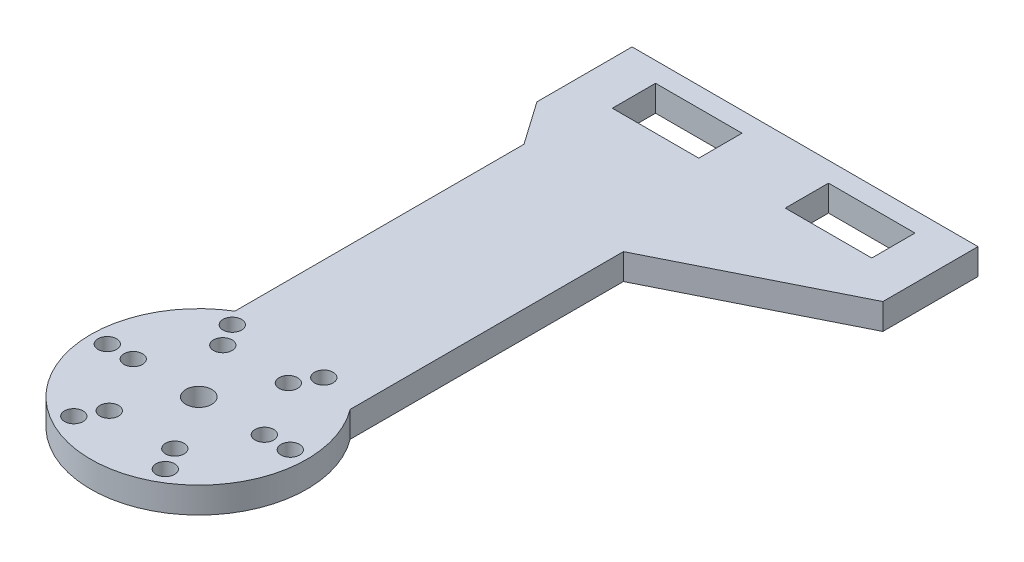
SolidWorks part; units mm, degrees
ref_plane "前视基准面" through (0, 0, 0) normal (0, 0, 1) x (1, 0, 0)
ref_plane "上视基准面" through (0, 0, 0) normal (0, 1, 0) x (1, 0, 0)
ref_plane "右视基准面" through (0, 0, 0) normal (1, 0, 0) x (0, 0, -1)
sketch "草图1" plane through (0, 0, 0) normal (0, 1, 0) x (1, 0, 0)
  line L0 (-143.0757, 0) -> (143.0757, 0) construction
  line L1 (0, 82.2875) -> (0, -82.2875) construction
  line L2 (-6.5, 10.6771) -> (-6.5, 44.1)
  line L3 (10, 7.5) -> (10, 39.1)
  line L4 (-6.5, 44.1) -> (-10, 49.0985)
  line L5 (-10, 49.0985) -> (-10, 60.1)
  line L6 (-10, 60.1) -> (30, 60.1)
  line L7 (30, 60.1) -> (30, 49.1)
  line L8 (30, 49.1) -> (10, 39.1)
  line L9 (-5, 57.8142) -> (-5, 52.8142)
  line L10 (-5, 52.8142) -> (5, 52.8142)
  line L11 (5, 52.8142) -> (5, 57.8142)
  line L13 (15, 57.8142) -> (15, 52.8142)
  line L14 (15, 52.8142) -> (25, 52.8142)
  line L15 (25, 52.8142) -> (25, 57.8142)
  line L16 (25, 57.8142) -> (15, 57.8142)
  line L18 (-5, 57.8142) -> (5, 57.8142)
  arc A0 (-6.5, 10.6771) -> (10, 7.5) centre (0, 0) ccw
  circle A2 centre (7.58, 0) radius 1.075
  circle A3 centre (10.58, 0) radius 1.075
  circle A14 centre (3.79, -6.5645) radius 1.075
  circle A15 centre (5.29, -9.1625) radius 1.075
  circle A16 centre (-3.79, -6.5645) radius 1.075
  circle A17 centre (-5.29, -9.1625) radius 1.075
  circle A18 centre (-7.58, 0) radius 1.075
  circle A19 centre (-10.58, 0) radius 1.075
  circle A20 centre (-3.79, 6.5645) radius 1.075
  circle A21 centre (-5.29, 9.1625) radius 1.075
  circle A22 centre (3.79, 6.5645) radius 1.075
  circle A23 centre (5.29, 9.1625) radius 1.075
  circle A24 centre (0, 0) radius 1.5
  point P4 (0, 0)
  point P8 (0, 0)
  point P37 (0, 0)
  point P53 (0, 0)
  dimension "D1" = 25
  dimension "D3" = 2.15
  dimension "D4" = 3
  dimension "D5" = 7.58
  dimension "D7" = 6.5
  dimension "D8" = 31.6
  dimension "D9" = 10
  dimension "D10" = 60.1
  dimension "D11" = 16
  dimension "D12" = 11
  dimension "D13" = 40
  dimension "D14" = 30
  dimension "D15" = 35
  dimension "D16" = 10
  dimension "D17" = 5
  dimension "D18" = 10
  dimension "D19" = 5
  dimension "D20" = 10
  dimension "D21" = 5
  dimension "D6" = 6
extrude "凸台-拉伸2" add sketch "草图1" along normal blind 3
